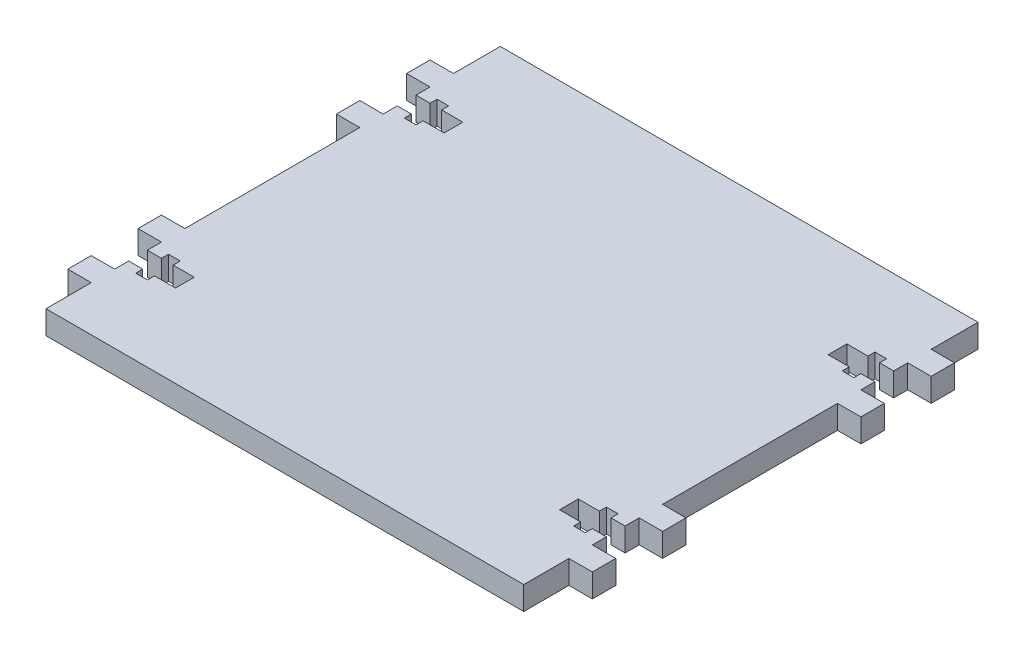
SolidWorks part; units mm, degrees
ref_plane "Front Plane" through (0, 0, 0) normal (0, 0, 1) x (1, 0, 0)
ref_plane "Top Plane" through (0, 0, 0) normal (0, 1, 0) x (1, 0, 0)
ref_plane "Right Plane" through (0, 0, 0) normal (1, 0, 0) x (0, 0, -1)
sketch "Sketch2" plane through (0, 0, 0) normal (0, 1, 0) x (1, 0, 0)
  line L16 (125.5661, 54.8651) -> (125.5661, 51.8651)
  line L17 (23.5661, 69.8651) -> (125.5661, 69.8651)
  line L42 (23.5661, 69.8651) -> (23.5661, 59.8651)
  line L43 (23.5661, -27.1349) -> (125.5661, -27.1349)
  line L44 (125.5661, 69.8651) -> (125.5661, 59.8651)
  line L49 (125.5661, 54.8651) -> (130.5661, 54.8651)
  line L50 (125.5661, 59.8651) -> (130.5661, 59.8651)
  line L51 (130.5661, 54.8651) -> (130.5661, 59.8651)
  line L52 (125.5661, 44.8651) -> (130.5661, 44.8651)
  line L53 (125.5661, 39.8651) -> (130.5661, 39.8651)
  line L54 (130.5661, 44.8651) -> (130.5661, 39.8651)
  line L55 (125.5661, 39.8651) -> (125.5661, 2.5191)
  line L56 (74.5661, 69.8651) -> (74.5661, -27.1349) construction
  line L57 (7.561, 21.1921) -> (125.5661, 21.1921) construction
  line L58 (23.5661, 39.8651) -> (18.5661, 39.8651)
  line L59 (18.5661, 44.8651) -> (18.5661, 39.8651)
  line L60 (23.5661, 44.8651) -> (18.5661, 44.8651)
  line L61 (18.5661, 54.8651) -> (18.5661, 59.8651)
  line L62 (23.5661, 54.8651) -> (18.5661, 54.8651)
  line L63 (23.5661, 59.8651) -> (18.5661, 59.8651)
  line L64 (130.5661, -12.4809) -> (130.5661, -17.4809)
  line L65 (125.5661, -17.4809) -> (130.5661, -17.4809)
  line L66 (125.5661, -12.4809) -> (130.5661, -12.4809)
  line L67 (130.5661, -2.4809) -> (130.5661, 2.5191)
  line L68 (125.5661, 2.5191) -> (130.5661, 2.5191)
  line L69 (125.5661, -2.4809) -> (130.5661, -2.4809)
  line L70 (23.5661, -17.4809) -> (18.5661, -17.4809)
  line L71 (23.5661, -12.4809) -> (18.5661, -12.4809)
  line L72 (23.5661, 2.5191) -> (18.5661, 2.5191)
  line L73 (23.5661, -2.4809) -> (18.5661, -2.4809)
  line L74 (18.5661, -12.4809) -> (18.5661, -17.4809)
  line L75 (18.5661, -2.4809) -> (18.5661, 2.5191)
  line L76 (125.5661, -2.4809) -> (125.5661, -5.4809)
  line L77 (125.5661, -17.4809) -> (125.5661, -27.1349)
  line L78 (23.5661, -17.4809) -> (23.5661, -27.1349)
  line L79 (23.5661, -2.4809) -> (23.5661, -5.4809)
  line L80 (23.5661, 39.8651) -> (23.5661, 2.5191)
  line L81 (23.5661, 54.8651) -> (23.5661, 51.8651)
  line L82 (109.561, 49.8651) -> (7.561, 49.8651) construction
  line L83 (125.5661, 51.8651) -> (122.5661, 51.8651)
  line L85 (125.5661, 47.8651) -> (122.5661, 47.8651)
  line L86 (115.5661, 51.8651) -> (115.5661, 47.8651)
  line L88 (122.5661, 51.8651) -> (122.5661, 53.3651)
  line L89 (122.5661, 53.3651) -> (120.0661, 53.3651)
  line L90 (120.0661, 51.8651) -> (120.0661, 53.3651)
  line L91 (120.0661, 51.8651) -> (115.5661, 51.8651)
  line L92 (122.5661, 47.8651) -> (122.5661, 46.3651)
  line L93 (122.5661, 46.3651) -> (120.0661, 46.3651)
  line L94 (120.0661, 47.8651) -> (120.0661, 46.3651)
  line L95 (120.0661, 47.8651) -> (115.5661, 47.8651)
  line L96 (125.5661, 47.8651) -> (125.5661, 44.8651)
  line L97 (26.5661, 51.8651) -> (26.5661, 53.3651)
  line L98 (29.0661, 51.8651) -> (29.0661, 53.3651)
  line L99 (26.5661, 53.3651) -> (29.0661, 53.3651)
  line L100 (23.5661, 51.8651) -> (26.5661, 51.8651)
  line L101 (23.5661, 47.8651) -> (26.5661, 47.8651)
  line L102 (26.5661, 47.8651) -> (26.5661, 46.3651)
  line L103 (29.0661, 47.8651) -> (29.0661, 46.3651)
  line L104 (26.5661, 46.3651) -> (29.0661, 46.3651)
  line L105 (29.0661, 47.8651) -> (33.5661, 47.8651)
  line L106 (33.5661, 51.8651) -> (33.5661, 47.8651)
  line L107 (29.0661, 51.8651) -> (33.5661, 51.8651)
  line L108 (23.5661, -9.4809) -> (26.5661, -9.4809)
  line L109 (26.5661, -9.4809) -> (26.5661, -10.9809)
  line L110 (29.0661, -9.4809) -> (29.0661, -10.9809)
  line L111 (26.5661, -10.9809) -> (29.0661, -10.9809)
  line L112 (29.0661, -9.4809) -> (33.5661, -9.4809)
  line L113 (33.5661, -9.4809) -> (33.5661, -5.4809)
  line L114 (29.0661, -5.4809) -> (33.5661, -5.4809)
  line L115 (29.0661, -5.4809) -> (29.0661, -3.9809)
  line L116 (26.5661, -5.4809) -> (26.5661, -3.9809)
  line L117 (26.5661, -3.9809) -> (29.0661, -3.9809)
  line L118 (23.5661, -5.4809) -> (26.5661, -5.4809)
  line L119 (120.0661, -9.4809) -> (120.0661, -10.9809)
  line L120 (122.5661, -10.9809) -> (120.0661, -10.9809)
  line L121 (122.5661, -9.4809) -> (122.5661, -10.9809)
  line L122 (125.5661, -9.4809) -> (122.5661, -9.4809)
  line L123 (125.5661, -5.4809) -> (122.5661, -5.4809)
  line L124 (122.5661, -5.4809) -> (122.5661, -3.9809)
  line L125 (122.5661, -3.9809) -> (120.0661, -3.9809)
  line L126 (120.0661, -5.4809) -> (120.0661, -3.9809)
  line L127 (120.0661, -5.4809) -> (115.5661, -5.4809)
  line L128 (115.5661, -9.4809) -> (115.5661, -5.4809)
  line L129 (120.0661, -9.4809) -> (115.5661, -9.4809)
  line L130 (23.5661, 47.8651) -> (23.5661, 44.8651)
  line L131 (23.5661, -9.4809) -> (23.5661, -12.4809)
  line L132 (125.5661, -9.4809) -> (125.5661, -12.4809)
  dimension "D1" = 102
  dimension "D2" = 97
  dimension "D3" = 3
  dimension "D4" = 3
  dimension "D5" = 10
  dimension "D6" = 5
  dimension "D7" = 10
  dimension "D8" = 10
  dimension "D9" = 2.5
  dimension "D10" = 1.5
extrude "Boss-Extrude3" add sketch "Sketch2" along normal blind 5
